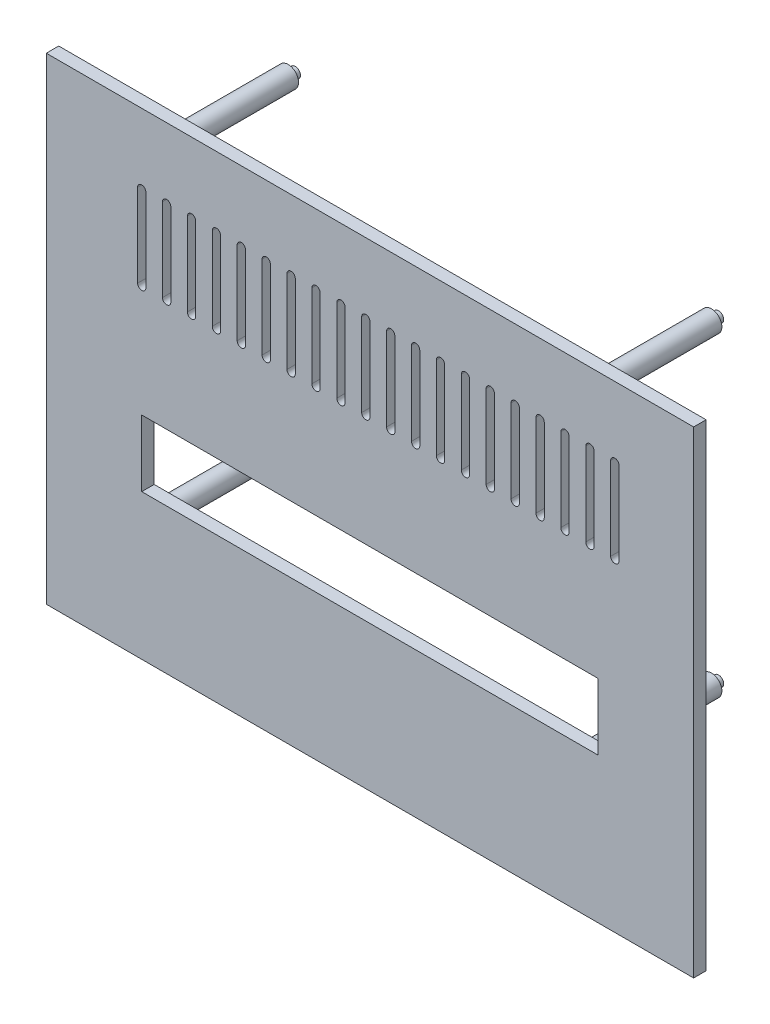
SolidWorks part; units mm, degrees
material "ABS"
ref_plane "前视基准面" through (0, 0, 0) normal (0, 0, 1) x (1, 0, 0)
ref_plane "上视基准面" through (0, 0, 0) normal (0, 1, 0) x (1, 0, 0)
ref_plane "右视基准面" through (0, 0, 0) normal (1, 0, 0) x (0, 0, -1)
sketch "草图1" plane through (0, 0, -2087.4817) normal (0, 0, 1) x (1, 0, 0)
  line L1 (73.6288, 67.7768) -> (217.6288, 67.7768)
  line L2 (73.6288, 67.7768) -> (73.6288, -36.2232)
  line L3 (73.6288, -36.2232) -> (217.6288, -36.2232)
  line L4 (217.6288, 67.7768) -> (217.6288, -36.2232)
  line L5 (220.6288, -39.2232) -> (70.6288, -39.2232)
  line L6 (220.6288, -39.2232) -> (220.6288, 70.7768)
  line L7 (220.6288, 70.7768) -> (70.6288, 70.7768)
  line L8 (70.6288, -39.2232) -> (70.6288, 70.7768)
sketch "草图2" plane through (0, 0, -2087.4817) normal (0, 0, 1) x (1, 0, 0)
  line L0 (90.6288, 35.7768) -> (90.6288, 55.7768) construction
  line L1 (67.6288, 72.7768) -> (223.6288, 72.7768)
  line L2 (67.6288, 72.7768) -> (67.6288, -42.2232)
  line L3 (67.6288, -42.2232) -> (223.6288, -42.2232)
  line L4 (223.6288, 72.7768) -> (223.6288, -42.2232)
  line L5 (90.6288, 8.7768) -> (200.6288, 8.7768)
  line L6 (90.6288, 8.7768) -> (90.6288, -7.2232)
  line L7 (90.6288, -7.2232) -> (200.6288, -7.2232)
  line L8 (200.6288, 8.7768) -> (200.6288, -7.2232)
  line L9 (89.6288, 35.7768) -> (89.6288, 55.7768)
  line L10 (91.6288, 35.7768) -> (91.6288, 55.7768)
  line L11 (96.6288, 35.7768) -> (96.6288, 55.7768) construction
  line L12 (95.6288, 35.7768) -> (95.6288, 55.7768)
  line L13 (97.6288, 35.7768) -> (97.6288, 55.7768)
  line L14 (102.6288, 35.7768) -> (102.6288, 55.7768) construction
  line L15 (101.6288, 35.7768) -> (101.6288, 55.7768)
  line L16 (103.6288, 35.7768) -> (103.6288, 55.7768)
  line L17 (108.6288, 35.7768) -> (108.6288, 55.7768) construction
  line L18 (107.6288, 35.7768) -> (107.6288, 55.7768)
  line L19 (109.6288, 35.7768) -> (109.6288, 55.7768)
  line L20 (114.6288, 35.7768) -> (114.6288, 55.7768) construction
  line L21 (113.6288, 35.7768) -> (113.6288, 55.7768)
  line L22 (115.6288, 35.7768) -> (115.6288, 55.7768)
  line L23 (120.6288, 35.7768) -> (120.6288, 55.7768) construction
  line L24 (119.6288, 35.7768) -> (119.6288, 55.7768)
  line L25 (121.6288, 35.7768) -> (121.6288, 55.7768)
  line L26 (126.6288, 35.7768) -> (126.6288, 55.7768) construction
  line L27 (125.6288, 35.7768) -> (125.6288, 55.7768)
  line L28 (127.6288, 35.7768) -> (127.6288, 55.7768)
  line L29 (132.6288, 35.7768) -> (132.6288, 55.7768) construction
  line L30 (131.6288, 35.7768) -> (131.6288, 55.7768)
  line L31 (133.6288, 35.7768) -> (133.6288, 55.7768)
  line L32 (138.6288, 35.7768) -> (138.6288, 55.7768) construction
  line L33 (137.6288, 35.7768) -> (137.6288, 55.7768)
  line L34 (139.6288, 35.7768) -> (139.6288, 55.7768)
  line L35 (144.6288, 35.7768) -> (144.6288, 55.7768) construction
  line L36 (143.6288, 35.7768) -> (143.6288, 55.7768)
  line L37 (145.6288, 35.7768) -> (145.6288, 55.7768)
  line L38 (150.6288, 35.7768) -> (150.6288, 55.7768) construction
  line L39 (149.6288, 35.7768) -> (149.6288, 55.7768)
  line L40 (151.6288, 35.7768) -> (151.6288, 55.7768)
  line L41 (156.6288, 35.7768) -> (156.6288, 55.7768) construction
  line L42 (155.6288, 35.7768) -> (155.6288, 55.7768)
  line L43 (157.6288, 35.7768) -> (157.6288, 55.7768)
  line L44 (162.6288, 35.7768) -> (162.6288, 55.7768) construction
  line L45 (161.6288, 35.7768) -> (161.6288, 55.7768)
  line L46 (163.6288, 35.7768) -> (163.6288, 55.7768)
  line L47 (168.6288, 35.7768) -> (168.6288, 55.7768) construction
  line L48 (167.6288, 35.7768) -> (167.6288, 55.7768)
  line L49 (169.6288, 35.7768) -> (169.6288, 55.7768)
  line L50 (174.6288, 35.7768) -> (174.6288, 55.7768) construction
  line L51 (173.6288, 35.7768) -> (173.6288, 55.7768)
  line L52 (175.6288, 35.7768) -> (175.6288, 55.7768)
  line L53 (180.6288, 35.7768) -> (180.6288, 55.7768) construction
  line L54 (179.6288, 35.7768) -> (179.6288, 55.7768)
  line L55 (181.6288, 35.7768) -> (181.6288, 55.7768)
  line L56 (186.6288, 35.7768) -> (186.6288, 55.7768) construction
  line L57 (185.6288, 35.7768) -> (185.6288, 55.7768)
  line L58 (187.6288, 35.7768) -> (187.6288, 55.7768)
  line L59 (192.6288, 35.7768) -> (192.6288, 55.7768) construction
  line L60 (191.6288, 35.7768) -> (191.6288, 55.7768)
  line L61 (193.6288, 35.7768) -> (193.6288, 55.7768)
  line L62 (198.6288, 35.7768) -> (198.6288, 55.7768) construction
  line L63 (197.6288, 35.7768) -> (197.6288, 55.7768)
  line L64 (199.6288, 35.7768) -> (199.6288, 55.7768)
  line L65 (204.6288, 35.7768) -> (204.6288, 55.7768) construction
  line L66 (203.6288, 35.7768) -> (203.6288, 55.7768)
  line L67 (205.6288, 35.7768) -> (205.6288, 55.7768)
  line L70 (153, -3) -> (153, 112) construction
  arc A0 (89.6288, 35.7768) -> (91.6288, 35.7768) centre (90.6288, 35.7768) ccw
  arc A1 (91.6288, 55.7768) -> (89.6288, 55.7768) centre (90.6288, 55.7768) ccw
  arc A2 (95.6288, 35.7768) -> (97.6288, 35.7768) centre (96.6288, 35.7768) ccw
  arc A3 (97.6288, 55.7768) -> (95.6288, 55.7768) centre (96.6288, 55.7768) ccw
  arc A4 (101.6288, 35.7768) -> (103.6288, 35.7768) centre (102.6288, 35.7768) ccw
  arc A5 (103.6288, 55.7768) -> (101.6288, 55.7768) centre (102.6288, 55.7768) ccw
  arc A6 (107.6288, 35.7768) -> (109.6288, 35.7768) centre (108.6288, 35.7768) ccw
  arc A7 (109.6288, 55.7768) -> (107.6288, 55.7768) centre (108.6288, 55.7768) ccw
  arc A8 (113.6288, 35.7768) -> (115.6288, 35.7768) centre (114.6288, 35.7768) ccw
  arc A9 (115.6288, 55.7768) -> (113.6288, 55.7768) centre (114.6288, 55.7768) ccw
  arc A10 (119.6288, 35.7768) -> (121.6288, 35.7768) centre (120.6288, 35.7768) ccw
  arc A11 (121.6288, 55.7768) -> (119.6288, 55.7768) centre (120.6288, 55.7768) ccw
  arc A12 (125.6288, 35.7768) -> (127.6288, 35.7768) centre (126.6288, 35.7768) ccw
  arc A13 (127.6288, 55.7768) -> (125.6288, 55.7768) centre (126.6288, 55.7768) ccw
  arc A14 (131.6288, 35.7768) -> (133.6288, 35.7768) centre (132.6288, 35.7768) ccw
  arc A15 (133.6288, 55.7768) -> (131.6288, 55.7768) centre (132.6288, 55.7768) ccw
  arc A16 (137.6288, 35.7768) -> (139.6288, 35.7768) centre (138.6288, 35.7768) ccw
  arc A17 (139.6288, 55.7768) -> (137.6288, 55.7768) centre (138.6288, 55.7768) ccw
  arc A18 (143.6288, 35.7768) -> (145.6288, 35.7768) centre (144.6288, 35.7768) ccw
  arc A19 (145.6288, 55.7768) -> (143.6288, 55.7768) centre (144.6288, 55.7768) ccw
  arc A20 (149.6288, 35.7768) -> (151.6288, 35.7768) centre (150.6288, 35.7768) ccw
  arc A21 (151.6288, 55.7768) -> (149.6288, 55.7768) centre (150.6288, 55.7768) ccw
  arc A22 (155.6288, 35.7768) -> (157.6288, 35.7768) centre (156.6288, 35.7768) ccw
  arc A23 (157.6288, 55.7768) -> (155.6288, 55.7768) centre (156.6288, 55.7768) ccw
  arc A24 (161.6288, 35.7768) -> (163.6288, 35.7768) centre (162.6288, 35.7768) ccw
  arc A25 (163.6288, 55.7768) -> (161.6288, 55.7768) centre (162.6288, 55.7768) ccw
  arc A26 (167.6288, 35.7768) -> (169.6288, 35.7768) centre (168.6288, 35.7768) ccw
  arc A27 (169.6288, 55.7768) -> (167.6288, 55.7768) centre (168.6288, 55.7768) ccw
  arc A28 (173.6288, 35.7768) -> (175.6288, 35.7768) centre (174.6288, 35.7768) ccw
  arc A29 (175.6288, 55.7768) -> (173.6288, 55.7768) centre (174.6288, 55.7768) ccw
  arc A30 (179.6288, 35.7768) -> (181.6288, 35.7768) centre (180.6288, 35.7768) ccw
  arc A31 (181.6288, 55.7768) -> (179.6288, 55.7768) centre (180.6288, 55.7768) ccw
  arc A32 (185.6288, 35.7768) -> (187.6288, 35.7768) centre (186.6288, 35.7768) ccw
  arc A33 (187.6288, 55.7768) -> (185.6288, 55.7768) centre (186.6288, 55.7768) ccw
  arc A34 (191.6288, 35.7768) -> (193.6288, 35.7768) centre (192.6288, 35.7768) ccw
  arc A35 (193.6288, 55.7768) -> (191.6288, 55.7768) centre (192.6288, 55.7768) ccw
  arc A36 (197.6288, 35.7768) -> (199.6288, 35.7768) centre (198.6288, 35.7768) ccw
  arc A37 (199.6288, 55.7768) -> (197.6288, 55.7768) centre (198.6288, 55.7768) ccw
  arc A38 (203.6288, 35.7768) -> (205.6288, 35.7768) centre (204.6288, 35.7768) ccw
  arc A39 (205.6288, 55.7768) -> (203.6288, 55.7768) centre (204.6288, 55.7768) ccw
  point P16 (90.6288, 45.7768)
  point P25 (96.6288, 45.7768)
  point P32 (102.6288, 45.7768)
  point P39 (108.6288, 45.7768)
  point P46 (114.6288, 45.7768)
  point P53 (120.6288, 45.7768)
  point P60 (126.6288, 45.7768)
  point P67 (132.6288, 45.7768)
  point P74 (138.6288, 45.7768)
  point P81 (144.6288, 45.7768)
  point P88 (150.6288, 45.7768)
  point P95 (156.6288, 45.7768)
  point P102 (162.6288, 45.7768)
  point P109 (168.6288, 45.7768)
  point P116 (174.6288, 45.7768)
  point P123 (180.6288, 45.7768)
  point P130 (186.6288, 45.7768)
  point P137 (192.6288, 45.7768)
  point P144 (198.6288, 45.7768)
  point P151 (204.6288, 45.7768)
  dimension "D1" = 1
  dimension "D3" = 3.6288
  dimension "D2" = 20
extrude "凸台-拉伸1" add sketch "草图2" along normal blind 3
extrude "凸台-拉伸2" add sketch "草图1" against normal blind 2
sketch "草图3" plane through (0, 0, -2087.4817) normal (0, 0, -1) x (-1, 0, 0)
  circle A0 centre (-196.6288, 65.7768) radius 2.5
  circle A1 centre (-94.6288, 65.7768) radius 2.5
  circle A2 centre (-94.6288, -10.2232) radius 2.5
  circle A3 centre (-196.6288, -10.2232) radius 2.5
  dimension "D1" = 5
extrude "凸台-拉伸3" add sketch "草图3" along normal blind 28.3
sketch "草图5" plane through (0, 0, -2115.7817) normal (0, 0, -1) x (-1, 0, 0)
  circle A0 centre (-196.6288, 65.7768) radius 1.25
  circle A1 centre (-94.6288, 65.7768) radius 1.25
  circle A2 centre (-94.6288, -10.2232) radius 1.25
  circle A3 centre (-196.6288, -10.2232) radius 1.25
  dimension "D1" = 2.5
extrude "凸台-拉伸4" add sketch "草图5" along normal blind 1.7
